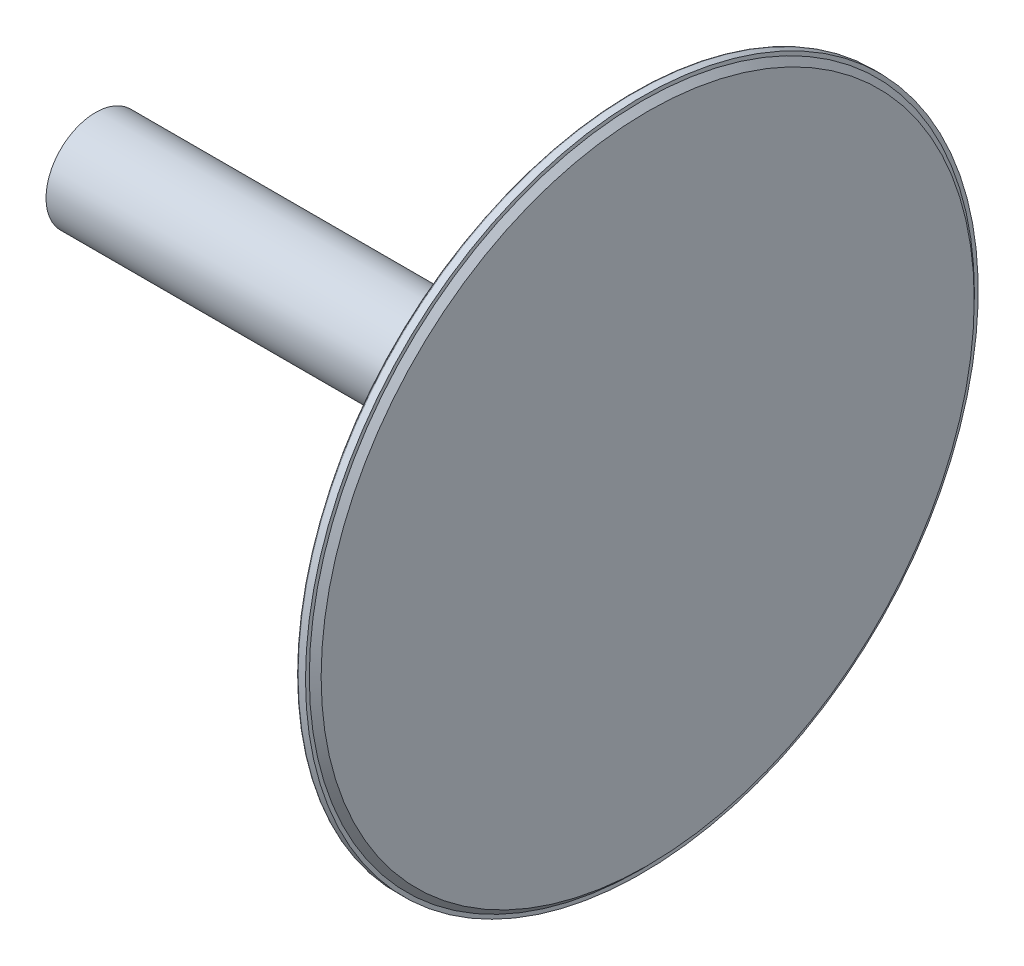
SolidWorks part; units mm, degrees
ref_plane "Front Plane" through (0, 0, 0) normal (0, 0, 1) x (1, 0, 0)
ref_plane "Top Plane" through (0, 0, 0) normal (0, 1, 0) x (1, 0, 0)
ref_plane "Right Plane" through (0, 0, 0) normal (1, 0, 0) x (0, 0, -1)
ref_plane "Plane4" through (0, 0, 0) normal (0, 0, -1) x (-1, 0, 0)
sketch "Sketch1" plane through (0, 0, 0) normal (0, 0, -1) x (-1, 0, 0)
  line L0 (-7.2, 56.0654) -> (-7.2, 0)
  line L1 (-7.2, 0) -> (2.8, 0)
  line L2 (2.8, 0) -> (2.8, 10)
  line L3 (2.8, 10) -> (-1.2, 10)
  line L4 (-1.2, 10) -> (-1.2, 9)
  line L5 (-1.2, 9) -> (-2.5, 9)
  line L6 (-2.5, 9) -> (-2.5, 10)
  line L7 (-2.5, 10) -> (-3.7, 10)
  line L8 (-3.7, 10) -> (-3.7, 56.25)
  line L9 (-3.7, 56.25) -> (-4.7, 56.25)
  line L11 (-4.7, 56.25) -> (-4.7, 57.75)
  line L12 (-4.7, 57.75) -> (-6.2, 57.75)
  line L13 (-6.2, 57.75) -> (-6.2, 57.1)
  line L14 (-7.2, 0) -> (2.8, 0) construction
  line L15 (-6.2, -57.1) -> (-6.2, 57.1) construction
  line L16 (-6.2, 57.1) -> (-7.2, 56.0654)
  line L17 (-7.2, -56.1) -> (-7.2, 56.1) construction
  line L18 (-6.2, -58) -> (-6.2, 58) construction
  line L19 (-6.2, 57.1) -> (-7.2, 56.1) construction
  point P30 (-2.5, 9.5)
  dimension "D1" = 3.5
  dimension "D2" = 1.5
  dimension "D3" = 1.5
  dimension "D4" = 56.0654
  dimension "D5" = 57.75
  dimension "D6" = 10
  dimension "D7" = 1.3
  dimension "D8" = 10
  dimension "D9" = 6
  dimension "D10" = 1
revolve "Revolve1" add sketch "Sketch1" angle 360 about L14
sketch "Sketch4" plane through (-2.8, 0, 0) normal (-1, 0, 0) x (0, 0, 1)
  circle A0 centre (0, 0) radius 8.5
extrude "Boss-Extrude2" add sketch "Sketch4" along normal blind 84.8
chamfer "Chamfer2" distance 0.273 angle 70 1 edges at (-2.8, 0, 10)
fillet "Fillet1" radius 0.25 1 edges at (4.7, 0, 57.75)
